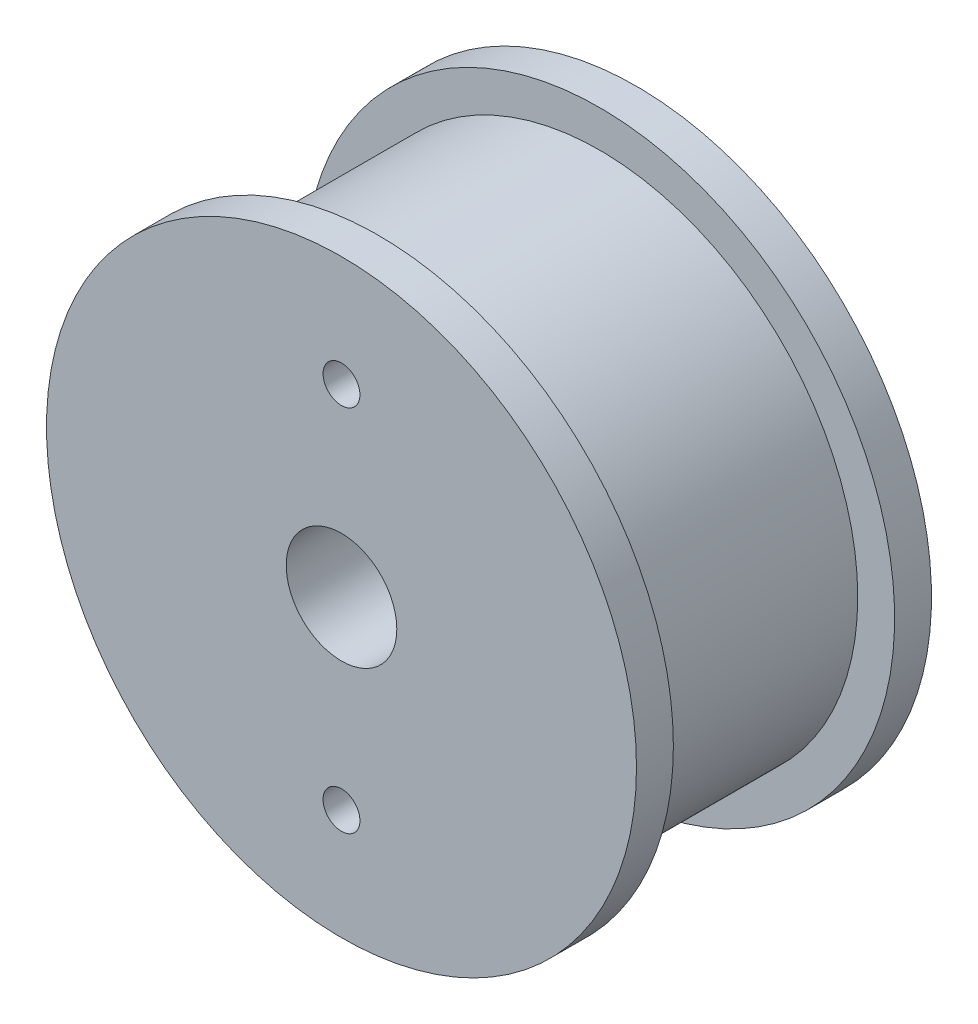
SolidWorks part; units mm, degrees
material "Alloy Steel"
ref_plane "Front Plane" through (0, 0, 0) normal (0, 0, 1) x (1, 0, 0)
ref_plane "Top Plane" through (0, 0, 0) normal (0, 1, 0) x (1, 0, 0)
ref_plane "Right Plane" through (0, 0, 0) normal (1, 0, 0) x (0, 0, -1)
sketch "Sketch1" plane through (0, 0, 0) normal (0, 0, 1) x (1, 0, 0)
  circle A0 centre (0, 0) radius 35
  circle A1 centre (0, 0) radius 12
  dimension "D1" = 70
  dimension "D2" = 24
extrude "Boss-Extrude1" add sketch "Sketch1" along normal blind 25
sketch "Sketch2" plane through (0, 0, 25) normal (0, 0, 1) x (1, 0, 0)
  circle A0 centre (0, 0) radius 35
  circle A1 centre (0, 0) radius 12 construction
  circle A2 centre (0, 0) radius 12
  dimension "D1" = 70
extrude "Boss-Extrude2" add sketch "Sketch2" along normal blind 5
sketch "Sketch4" plane through (0, 0, 30) normal (0, 0, 1) x (1, 0, 0)
  circle A0 centre (0, 0) radius 7.5
  circle A1 centre (0, 0) radius 12 construction
  circle A2 centre (0, 0) radius 12
  dimension "D1" = 15
extrude "Boss-Extrude4" add sketch "Sketch4" against normal blind 10
sketch "Sketch5" plane through (0, 0, 30) normal (0, 0, 1) x (1, 0, 0)
  circle A0 centre (0, 0) radius 40
  circle A1 centre (0, 0) radius 7.5 construction
  circle A2 centre (0, 0) radius 7.5
  dimension "D1" = 80
extrude "Boss-Extrude5" add sketch "Sketch5" along normal blind 5
sketch "Sketch6" plane through (0, 0, 0) normal (0, 0, -1) x (-1, 0, 0)
  circle A0 centre (0, 0) radius 40 construction
  circle A1 centre (0, 0) radius 12 construction
  circle A2 centre (0, 0) radius 40
  circle A3 centre (0, 0) radius 12
extrude "Boss-Extrude6" add sketch "Sketch6" along normal blind 5
sketch "Sketch7" plane through (0, 0, -5) normal (0, 0, -1) x (-1, 0, 0)
  line L0 (0, 32.7506) -> (0, -43.1994) construction
  circle A0 centre (0, 0) radius 25 construction
  circle A1 centre (0, 25) radius 2.5
  circle A2 centre (0, -25) radius 2.5
  dimension "D1" = 50
  dimension "D2" = 5
  dimension "D3" = 5
extrude "Cut-Extrude1" cut sketch "Sketch7" against normal through all
